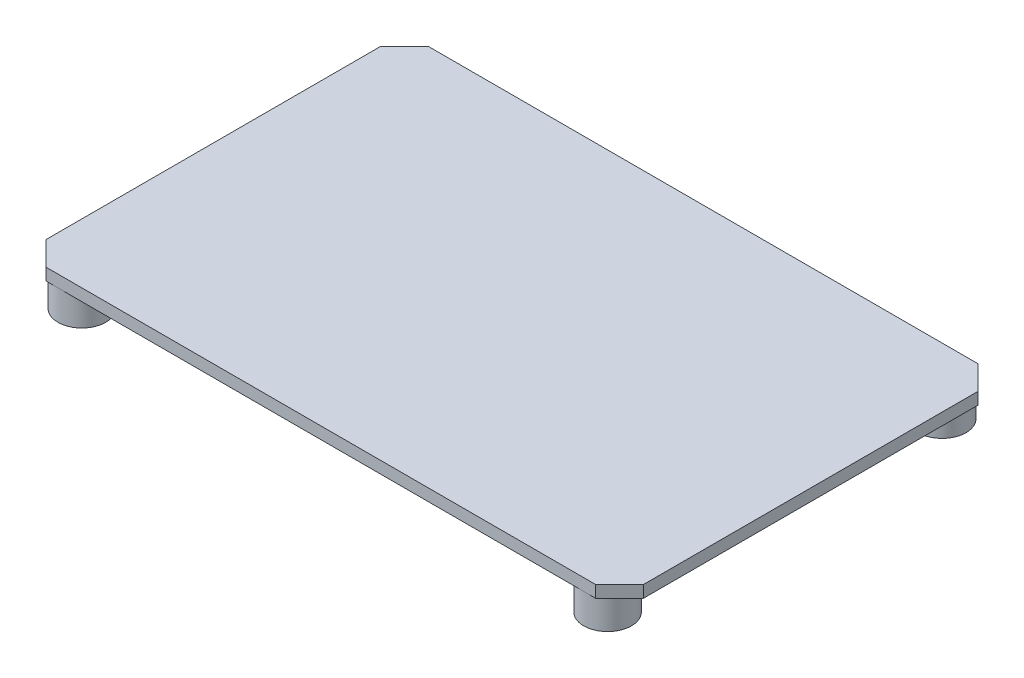
SolidWorks part; units mm, degrees
ref_plane "Front Plane" through (0, 0, 0) normal (0, 0, 1) x (1, 0, 0)
ref_plane "Top Plane" through (0, 0, 0) normal (0, 1, 0) x (1, 0, 0)
ref_plane "Right Plane" through (0, 0, 0) normal (1, 0, 0) x (0, 0, -1)
ref_plane "PZ17_4" through (0, 17.4, 0) normal (0, 1, 0) x (1, 0, 0)
sketch "Sketch1" plane through (0, 17.4, 0) normal (0, 1, 0) x (1, 0, 0)
  line L0 (-46, -84) -> (46, -84)
  line L1 (46, -84) -> (50, -80)
  line L2 (50, -80) -> (50, -24)
  line L3 (50, -24) -> (46, -20)
  line L4 (46, -20) -> (-46, -20)
  line L5 (-46, -20) -> (-50, -24)
  line L6 (-50, -24) -> (-50, -80)
  line L7 (-50, -80) -> (-46, -84)
extrude "Shade Plate" add sketch "Sketch1" along normal blind 2
ref_plane "PZ12_4" through (0, 12.4, 0) normal (0, 1, 0) x (1, 0, 0)
sketch "Sketch2" plane through (0, 12.4, 0) normal (0, 1, 0) x (1, 0, 0)
  circle A0 centre (-44, -24) radius 4
  circle A1 centre (-44, -80) radius 4
  circle A2 centre (44, -24) radius 4
  circle A3 centre (44, -80) radius 4
extrude "Posts" add sketch "Sketch2" along normal blind 5.1
ref_plane "PZ11_9" through (0, 11.9, 0) normal (0, 1, 0) x (1, 0, 0)
sketch "Sketch3" plane through (0, 11.9, 0) normal (0, 1, 0) x (1, 0, 0)
  circle A0 centre (-44, -24) radius 1.25
  circle A1 centre (-44, -80) radius 1.25
  circle A2 centre (44, -24) radius 1.25
  circle A3 centre (44, -80) radius 1.25
extrude "Post Pilots" cut sketch "Sketch3" along normal blind 6.5
equation "\"BOARD_REAR\" = 86.0"
equation "\"BOARD_FRONT\" = 41.0"
equation "\"BOARD_END\" = 22.0"
equation "\"BOARD_ANGLED\" = 30.0"
equation "\"BOARD_DEPTH\" = 41.8431"
equation "\"PCB_T\" = 1.6"
equation "\"ABOVE_PCB\" = 14.0"
equation "\"BELOW_PCB\" = 6.0"
equation "\"MID_PARTS_H\" = 9.0"
equation "\"BOARD_HOLE_PILOT\" = 1.6"
equation "\"J2_X\" = 19.0"
equation "\"DUPONT_DROP\" = 14.0"
equation "\"BEND_R\" = 5.0"
equation "\"BOARD_GAP\" = 3.0"
equation "\"TOF_FOV\" = 25.0"
equation "\"TOF_MARGIN_DEG\" = 5.0"
equation "\"TOF_WIN_MARGIN\" = 1.0"
equation "\"TOF_Z\" = 9.0"
equation "\"TOF_SIDE_BEARING\" = 90.0"
equation "\"TOF_CONE_LEN\" = 70.0"
equation "\"CAM_W\" = 29.2"
equation "\"CAM_H\" = 28.2"
equation "\"CAM_D\" = 12.35"
equation "\"CAM_FRONT_Y\" = 43.0"
equation "\"CAM_BOTTOM_Z\" = 17.0"
equation "\"CAM_LENS_UP\" = 11.6"
equation "\"CAM_LENS_OPEN\" = 9.6"
equation "\"CAM_HFOV\" = 53.5"
equation "\"CAM_VFOV\" = 41.41"
equation "\"CAM_FOV_MARGIN\" = 3.0"
equation "\"CAM_FIT\" = 0.3"
equation "\"RIBBON_W\" = 16.0"
equation "\"RIBBON_T\" = 0.3"
equation "\"RIBBON_LEN\" = 150.0"
equation "\"RIBBON_EXIT_Y\" = 35.0"
equation "\"WALL\" = 2.4"
equation "\"HEAD_X\" = 48.4"
equation "\"HEAD_REAR_Y\" = -11.9"
equation "\"CAM_FOAM\" = 2.8"
equation "\"HEAD_FRONT_Y\" = 48.2"
equation "\"HEAD_TOP_Z\" = 50.6"
equation "\"HEAD_BOT_Z\" = -28.4"
equation "\"HEAD_SPLIT_Z\" = -4.0"
equation "\"SKIRT_T\" = 1.2"
equation "\"SKIRT_H\" = 3.0"
equation "\"SKIRT_FIT\" = 0.3"
equation "\"VISOR\" = 7.8"
equation "\"VISOR_Z\" = 40.0"
equation "\"ROOF_SLOPE_Y\" = 40.0"
equation "\"ROOF_CHAMFER\" = 10.0"
equation "\"REAR_CHAMFER\" = 10.0"
equation "\"CORNER_CHAMFER\" = 6.0"
equation "\"LOWER_SIDE_FACET\" = 6.0"
equation "\"LIGHTBAR_DEPTH\" = 1.0"
equation "\"HOOD_Z\" = 14.0"
equation "\"HOOD_L\" = 6.0"
equation "\"SIDE_HOOD_L\" = 4.0"
equation "\"INSERT_M3_D\" = 4.0"
equation "\"INSERT_M3_L\" = 6.0"
equation "\"M3_CLEAR\" = 3.4"
equation "\"M2_PILOT\" = 1.6"
equation "\"M25_PILOT\" = 2.2"
equation "\"BOX_X\" = 72.4"
equation "\"BOX_FRONT_Y\" = -11.9"
equation "\"BOX_REAR_Y\" = -154.4"
equation "\"BOX_BOT_Z\" = -28.4"
equation "\"BOX_TOP_Z\" = 10.0"
equation "\"LID_T\" = 2.4"
equation "\"LID_SKIRT\" = 1.6"
equation "\"LID_TONGUE_H\" = 3.0"
equation "\"LID_FIT\" = 0.3"
equation "\"GNSS_WIN_T\" = 1.2"
equation "\"DIVIDER_Y\" = -86.0"
equation "\"PI_X0\" = -40.0"
equation "\"PI_X1\" = 45.0"
equation "\"PI_Y1\" = -26.3"
equation "\"PI_Y0\" = -82.3"
equation "\"PI_STANDOFF\" = 8.0"
equation "\"ESP_X0\" = -46.0"
equation "\"ESP_Y0\" = -149.0"
equation "\"ESP_L\" = 75.0"
equation "\"ESP_W\" = 52.0"
equation "\"ESP_STANDOFF\" = 12.0"
equation "\"BOX_REAR_CHAMFER\" = 8.0"
equation "\"BOX_REAR_FACET\" = 4.0"
equation "\"VENT_UPSTAND\" = 3.0"
equation "\"TUBE_D\" = 22.2"
equation "\"TUBE_LINER\" = 1.0"
equation "\"MOUNT_Y\" = -70.0"
equation "\"RAIL_W\" = 30.0"
equation "\"RAIL_W2\" = 38.0"
equation "\"RAIL_H\" = 6.0"
equation "\"SLIDE\" = 0.3"
equation "\"STOP_T\" = 6.0"
equation "\"CLAMP_W\" = 40.0"
equation "\"CLAMP_HALF\" = 20.0"
equation "\"CLAMP_DROP\" = 12.0"
equation "\"CAP_T\" = 12.0"
equation "\"CLAMP_BOLT_OFF\" = 16.6"
equation "\"M5_INSERT_D\" = 6.4"
equation "\"M5_CLEAR\" = 5.5"
equation "\"LOCK_D\" = 3.3"
equation "\"POD_TILT_DEG\" = 0.0"
equation "\"PRINT_LIMIT\" = 180.0"
